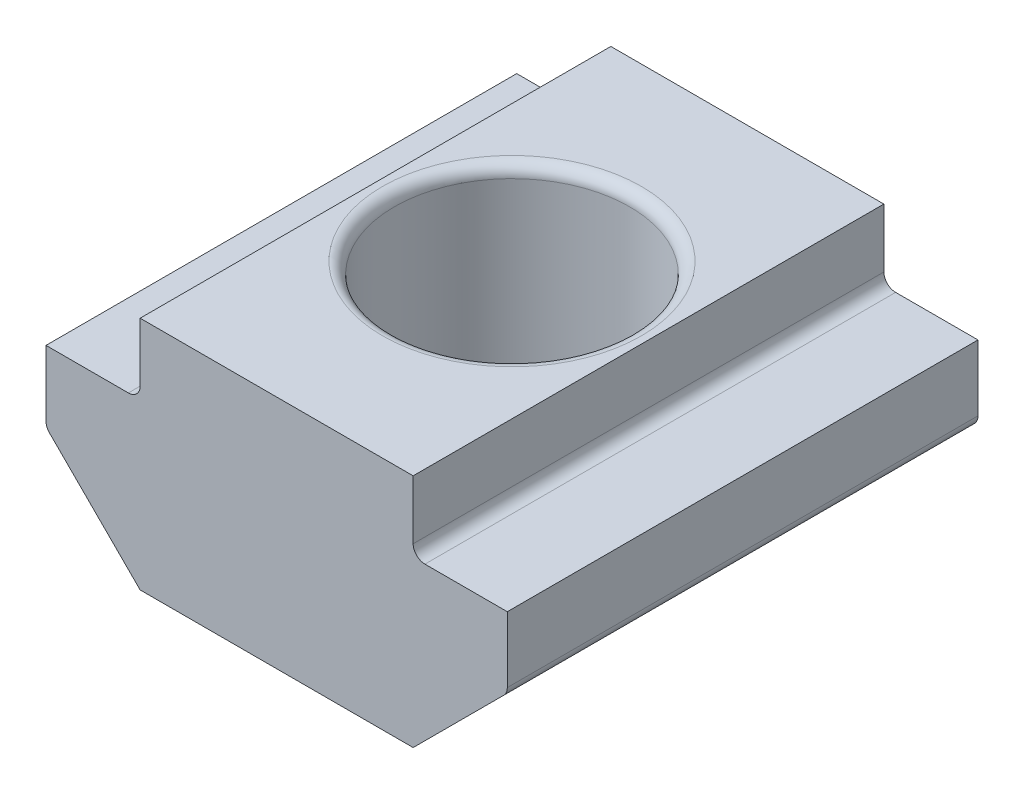
SolidWorks part; units mm, degrees
ref_plane "Front Plane" through (0, 0, 0) normal (0, 0, 1) x (1, 0, 0)
ref_plane "Top Plane" through (0, 0, 0) normal (0, 1, 0) x (1, 0, 0)
ref_plane "Right Plane" through (0, 0, 0) normal (1, 0, 0) x (0, 0, -1)
sketch "Sketch1" plane through (0, 0, 0) normal (0, 0, 1) x (1, 0, 0)
  line L1 (-2.9, -0.75) -> (2.9, -0.75) construction
  line L2 (-2.9, -0.75) -> (-2.9, 0.75)
  line L3 (-2.9, 0.75) -> (2.9, 0.75)
  line L4 (2.9, -0.75) -> (2.9, 0.75)
  line L5 (-2.9, -0.75) -> (2.9, 0.75) construction
  line L6 (-2.9, 0.75) -> (2.9, -0.75) construction
  line L7 (-2.9, -0.75) -> (-4.9, -0.75)
  line L11 (-4.9, -0.75) -> (-4.9, -2.25)
  line L12 (-4.9, -2.25) -> (-2.9, -4.25)
  line L15 (0, 1.3584) -> (0, -1.6026) construction
  line L16 (-2.9, -4.25) -> (2.9, -4.25)
  line L17 (4.9, -2.25) -> (2.9, -4.25)
  line L18 (4.9, -0.75) -> (4.9, -2.25)
  line L19 (2.9, -0.75) -> (4.9, -0.75)
  point P0 (0, 0)
  point P15 (0, -4.25)
  dimension "D1" = 5.8
  dimension "D2" = 5
  dimension "D3" = 9.8
  dimension "D4" = 1.5
  dimension "D5" = 135
  dimension "D6" = 3.5
extrude "Boss-Extrude1" add sketch "Sketch1" along normal mid plane 10
sketch "Sketch2" plane through (0, 0, 0) normal (0, 1, 0) x (1, 0, 0)
  circle A0 centre (0, 0) radius 2.5
  dimension "D1" = 5
extrude "Cut-Extrude1" cut sketch "Sketch2" against normal through all both and the other way through all
fillet "Fillet1" radius 0.25 4 edges at (4.9, -2.25, 0) (-4.9, -2.25, 0) (-2.9, -0.75, 0) (2.9, -0.75, 0)
fillet "Fillet2" radius 0.25 2 edges at (0, 0.75, 2.5) (0, -4.25, 2.5)
